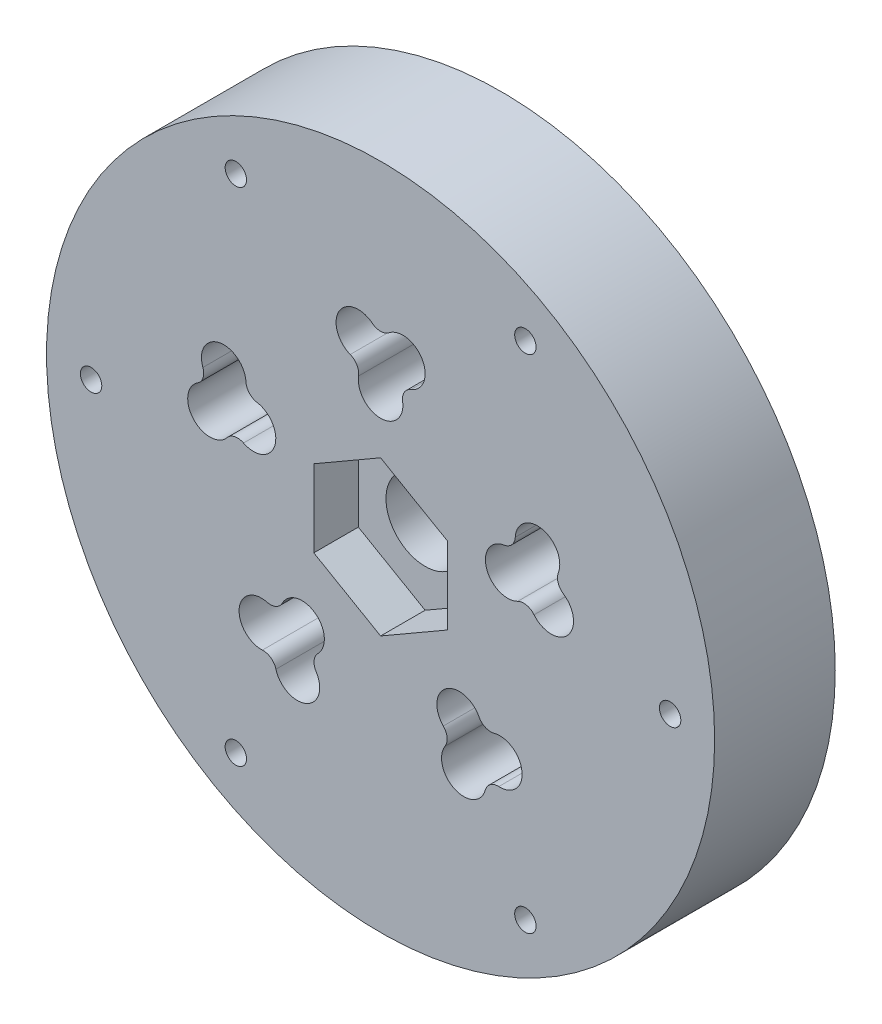
SolidWorks part; units mm, degrees
ref_plane "Plano frontal" through (0, 0, 0) normal (0, 0, 1) x (1, 0, 0)
ref_plane "Plano superior" through (0, 0, 0) normal (0, 1, 0) x (1, 0, 0)
ref_plane "Plano direito" through (0, 0, 0) normal (1, 0, 0) x (0, 0, -1)
sketch "Esboço1" plane through (0, 0, 0) normal (0, 0, 1) x (1, 0, 0)
  circle A0 centre (0, 0) radius 75 construction
  circle A1 centre (0, 0) radius 75
extrude "Ressalto-extrusão1" add sketch "Esboço1" against normal up to surface (27.075 mm away)
sketch "Esboço2" plane through (0, 0, 0) normal (0, 0, 1) x (1, 0, 0)
  circle A0 centre (0, 0) radius 8.8
  dimension "D1" = 17.6
extrude "Corte-extrusão1" cut sketch "Esboço2" against normal through all
sketch "Esboço3" plane through (0, 0, 0) normal (0, 0, 1) x (1, 0, 0)
  line L1 (0, 17.3205) -> (-15, 8.6603)
  line L2 (-15, 8.6603) -> (-15, -8.6603)
  line L3 (-15, -8.6603) -> (0, -17.3205)
  line L4 (0, -17.3205) -> (15, -8.6603)
  line L5 (15, -8.6603) -> (15, 8.6603)
  line L6 (15, 8.6603) -> (0, 17.3205)
  circle A0 centre (0, 0) radius 15 construction
  dimension "D1" = 30
extrude "Corte-extrusão2" cut sketch "Esboço3" against normal blind 10
hole_wizard "Rebaixo para SHCS M41" positions "Esboço4" profile "Esboço5" counterbore size "M4" standard "Ansi Metric" end condition through all
sketch "Esboço4" plane through (0, 0, -27.075) normal (0, 0, -1) x (-1, 0, 0)
  point P4 (-65, 0)
  point P7 (-32.5, 56.2917)
  point P10 (32.5, 56.2917)
  point P13 (65, 0)
  point P16 (-32.5, -56.2917)
  point P22 (32.5, -56.2917)
sketch "Esboço5" plane through (65, 0, -27.075) normal (1, 0, 0) x (0, 1, 0)
  line L0 (0, 0) -> (0, 27.075)
  line L1 (0, 27.075) -> (2.4, 27.075)
  line L3 (2.4, 27.075) -> (2.4, 4)
  line L4 (4, 4) -> (2.4, 4)
  line L5 (4, 4) -> (4, 0.025)
  line L6 (4, 0.025) -> (4.025, 0)
  line L7 (4.025, 0) -> (0, 0)
  line L8 (-4, 0.025) -> (-4.025, 0) construction
  line L11 (0, -6.35) -> (0, 107.95) construction
  dimension "Thru Hole Dia." = 4.8
  dimension "Thru Hole Depth" = 27.075
  dimension "C'Bore Dia." = 8
  dimension "C'Bore Depth" = 4
  dimension "Near C'Sink Dia." = 8.05
  dimension "Near C'Sink Angle" = 90
sketch "Esboço6" plane through (0, 0, -27.075) normal (0, 0, -1) x (-1, 0, 0)
  arc A0 (-1.875, 42.5634) -> (-6.8177, 34.0024) centre (-5, 38.6603) ccw
  arc A1 (6.8177, 34.0024) -> (1.875, 42.5634) centre (5, 38.6603) ccw
  arc A2 (-4.9427, 30.7548) -> (4.9427, 30.7548) centre (0, 30) ccw
  arc A3 (-1.875, 42.5634) -> (1.875, 42.5634) centre (0, 44.9053) ccw
  arc A4 (6.8177, 34.0024) -> (4.9427, 30.7548) centre (7.9083, 31.2076) ccw
  arc A5 (-4.9427, 30.7548) -> (-6.8177, 34.0024) centre (-7.9083, 31.2076) ccw
  dimension "D1" = 10
  dimension "D2" = 10
  dimension "D3" = 10
  dimension "D4" = 6
  dimension "D5" = 6
  dimension "D6" = 6
  dimension "D7" = 30
extrude "Corte-extrusão3" cut sketch "Esboço6" against normal through all
ref_axis "Eixo1" through (0, 0, -10) along (0, 0, -1)
pattern_circular "PadrãoCircular1" count 5 over 360 about axis through (0, 0, 0) along (0, 0, 1) of "Corte-extrusão3"
sketch "Esboço9" plane through (0, 0, 0) normal (0, 1, 0) x (1, 0, 0)
  line L0 (75, 27.075) -> (-75, 27.075) construction
  circle A0 centre (-53.5, 27.075) radius 4
  dimension "D1" = 8
  dimension "D2" = 53.5
revolve "Corte-Revolução1" cut sketch "Esboço9" angle 360 about axis through (0, 0, -10) along (0, 0, -1)
